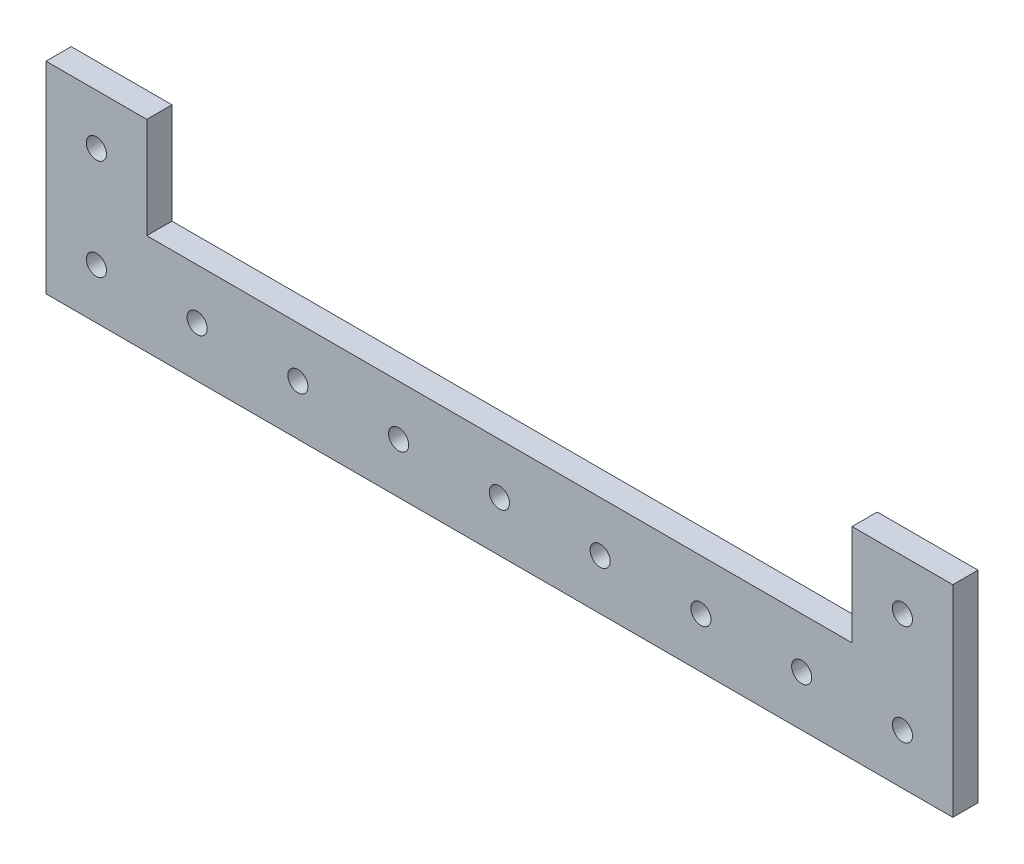
SolidWorks part; units mm, degrees
ref_plane "Front Plane" through (0, 0, 0) normal (0, 0, 1) x (1, 0, 0)
ref_plane "Top Plane" through (0, 0, 0) normal (0, 1, 0) x (1, 0, 0)
ref_plane "Right Plane" through (0, 0, 0) normal (1, 0, 0) x (0, 0, -1)
sketch "Sketch1" plane through (0, 0, 0) normal (0, 0, 1) x (1, 0, 0)
  line L0 (0, 0) -> (0, 50.8)
  line L1 (0, 50.8) -> (25.4, 50.8)
  line L2 (25.4, 50.8) -> (25.4, 25.4)
  line L5 (228.6, 0) -> (0, 0)
  line L6 (25.4, 25.4) -> (203.2, 25.4)
  line L7 (203.2, 25.4) -> (203.2, 50.8)
  line L8 (203.2, 50.8) -> (228.6, 50.8)
  line L9 (228.6, 50.8) -> (228.6, 0)
  dimension "D1" = 50.8
  dimension "D2" = 25.4
  dimension "D3" = 25.4
  dimension "3" = 228.6
extrude "Boss-Extrude1" add sketch "Sketch1" along normal blind 6.35
sketch "Sketch2" plane through (0, 0, 6.35) normal (0, 0, 1) x (1, 0, 0)
  line L0 (25.4, 50.8) -> (0, 50.8) construction
  line L1 (25.4, 25.4) -> (25.4, 50.8) construction
  line L2 (0, 0) -> (228.6, 0) construction
  line L3 (114.3, 25.4) -> (114.3, 0) construction
  line L6 (203.2, 25.4) -> (25.4, 25.4) construction
  line L7 (0, 0) -> (228.6, 0) construction
  circle A0 centre (12.7, 38.1) radius 2.54
  circle A1 centre (12.7, 12.7) radius 2.54
  circle A11 centre (38.1, 12.7) radius 2.54
  circle A12 centre (63.5, 12.7) radius 2.54
  circle A13 centre (88.9, 12.7) radius 2.54
  circle A14 centre (114.3, 12.7) radius 2.54
  circle A15 centre (139.7, 12.7) radius 2.54
  circle A16 centre (165.1, 12.7) radius 2.54
  circle A17 centre (190.5, 12.7) radius 2.54
  circle A18 centre (215.9, 12.7) radius 2.54
  circle A19 centre (215.9, 38.1) radius 2.54
  dimension "D1" = 5.08
  dimension "D2" = 12.7
  dimension "D3" = 12.7
  dimension "D4" = 12.7
  dimension "D5" = 9
extrude "Cut-Extrude1" cut sketch "Sketch2" against normal through all
